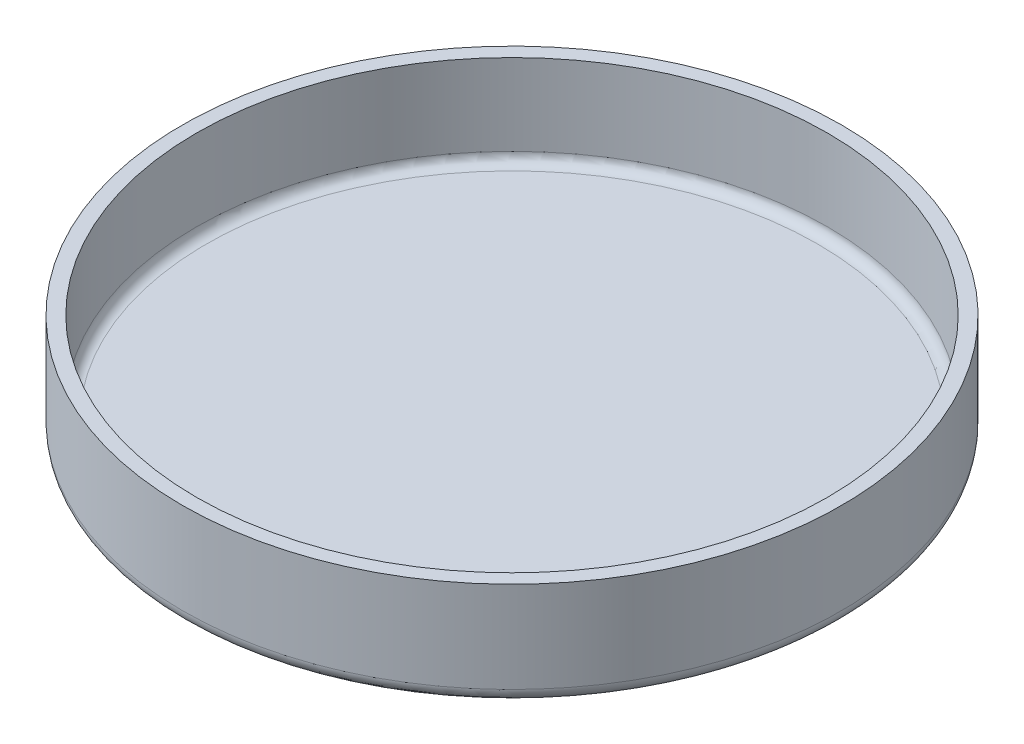
SolidWorks part; units mm, degrees
ref_plane "Alzado" through (0, 0, 0) normal (0, 0, 1) x (1, 0, 0)
ref_plane "Planta" through (0, 0, 0) normal (0, 1, 0) x (1, 0, 0)
ref_plane "Vista lateral" through (0, 0, 0) normal (1, 0, 0) x (0, 0, -1)
sketch "Croquis1" plane through (0, 0, 0) normal (0, 0, 1) x (1, 0, 0)
  line L0 (0, 0) -> (0, 24.4085) construction
  line L1 (45, 0) -> (0, 0)
  line L2 (0, 0) -> (0, 2)
  line L3 (0, 2) -> (43.5858, 2)
  line L6 (47, 2) -> (47, 15)
  line L7 (47, 15) -> (45, 15)
  line L8 (45, 3.4142) -> (45, 15)
  arc A0 (47, 2) -> (45, 0) centre (45, 2) cw
  arc A1 (45, 3.4142) -> (43.5858, 2) centre (43.5858, 3.4142) cw
  point P10 (47, 0)
  dimension "D4" = 2
  dimension "D1" = 15
  dimension "D2" = 47
  dimension "D3" = 2
revolve "Revolución1" add sketch "Croquis1" angle 360 about L0
